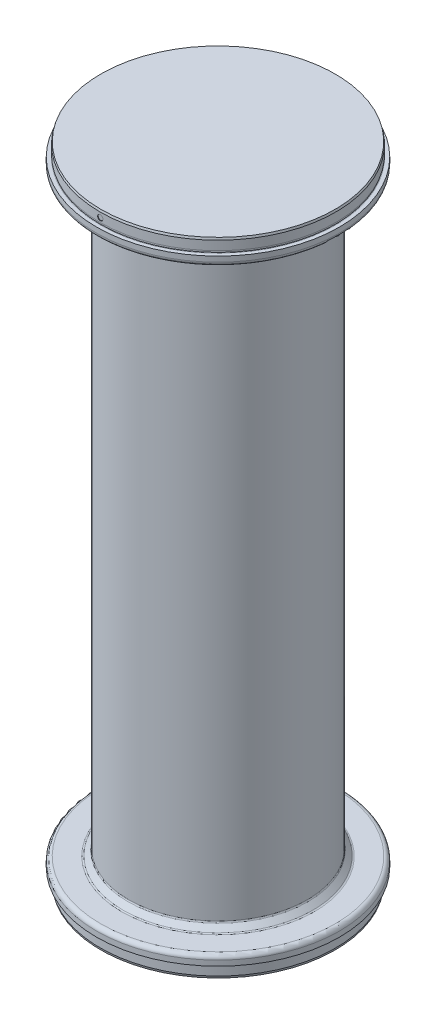
SolidWorks part; units mm, degrees
ref_plane "Front Plane" through (0, 0, 0) normal (0, 0, 1) x (1, 0, 0)
ref_plane "Top Plane" through (0, 0, 0) normal (0, 1, 0) x (1, 0, 0)
ref_plane "Right Plane" through (0, 0, 0) normal (1, 0, 0) x (0, 0, -1)
ref_plane "Plane4" through (0, 0, 0) normal (0, 0, -1) x (-1, 0, 0)
sketch "Sketch1" plane through (0, 0, 0) normal (0, 0, -1) x (-1, 0, 0)
  line L0 (-56, -299.7) -> (0, -299.7)
  line L1 (0, -299.7) -> (0, -5.3)
  line L2 (0, -5.3) -> (-56, -5.3)
  line L3 (-55.7321, -5.3779) -> (-55.7321, -6.2221)
  line L4 (-56, -6.3) -> (-57.75, -6.3)
  line L5 (-57.75, -6.3) -> (-57.75, -10.8)
  line L6 (-57.75, -10.8) -> (-45.4, -10.8)
  line L7 (-45.4, -10.8) -> (-42.5, -13.7)
  line L8 (-42.5, -13.7) -> (-42.5, -291.3)
  line L9 (-42.5, -291.3) -> (-45.4, -294.2)
  line L10 (-45.4, -294.2) -> (-57.75, -294.2)
  line L11 (-57.75, -294.2) -> (-57.75, -298.7)
  line L12 (-57.75, -298.7) -> (-56, -298.7)
  line L13 (-55.7321, -298.7779) -> (-55.7321, -299.6221)
  line L14 (0, -299.7) -> (0, -5.3) construction
  arc A0 (-56, -5.3) -> (-55.7321, -5.3779) centre (-56, -5.8) cw
  arc A1 (-55.7321, -6.2221) -> (-56, -6.3) centre (-56, -5.8) cw
  arc A2 (-56, -298.7) -> (-55.7321, -298.7779) centre (-56, -299.2) cw
  arc A3 (-55.7321, -299.6221) -> (-56, -299.7) centre (-56, -299.2) cw
revolve "Revolve1" add sketch "Sketch1" angle 360 about L14
sketch "Sketch2" plane through (0, -299.7, 0) normal (0, -1, 0) x (1, 0, 0)
  circle A0 centre (0, 0) radius 56
extrude "Boss-Extrude1" add sketch "Sketch2" along normal blind 5.3
sketch "Sketch4" plane through (0, -5.3, 0) normal (0, 1, 0) x (-1, 0, 0)
  circle A0 centre (0, 0) radius 56
extrude "Boss-Extrude2" add sketch "Sketch4" along normal blind 5.3
sketch "Sketch6" plane through (0, 0, 0) normal (1, 0, 0) x (0, 0, -1)
  line L0 (-56, -3.3) -> (-56, -4.55)
  line L1 (-56, -4.55) -> (-55.718, -4.55)
  line L2 (-55.718, -4.55) -> (-55.718, -3.3)
  line L3 (-55.718, -3.3) -> (-56, -3.3)
  line L4 (-55.718, -3.3) -> (-56, -3.3) construction
revolve "Cut-Revolve1" cut sketch "Sketch6" angle 360 about L4
chamfer "Chamfer1" distance 0.2679 angle 75 2 edges at (0, 0, 56) (0, -305, -56)
fillet "Fillet1" radius 1 4 edges at (0, -10.8, 45.4) (0, -294.2, 45.4) (0, -291.3, 42.5) (0, -13.7, 42.5)
fillet "Fillet3" radius 2 2 edges at (0, -10.8, 57.75) (0, -294.2, 57.75)
